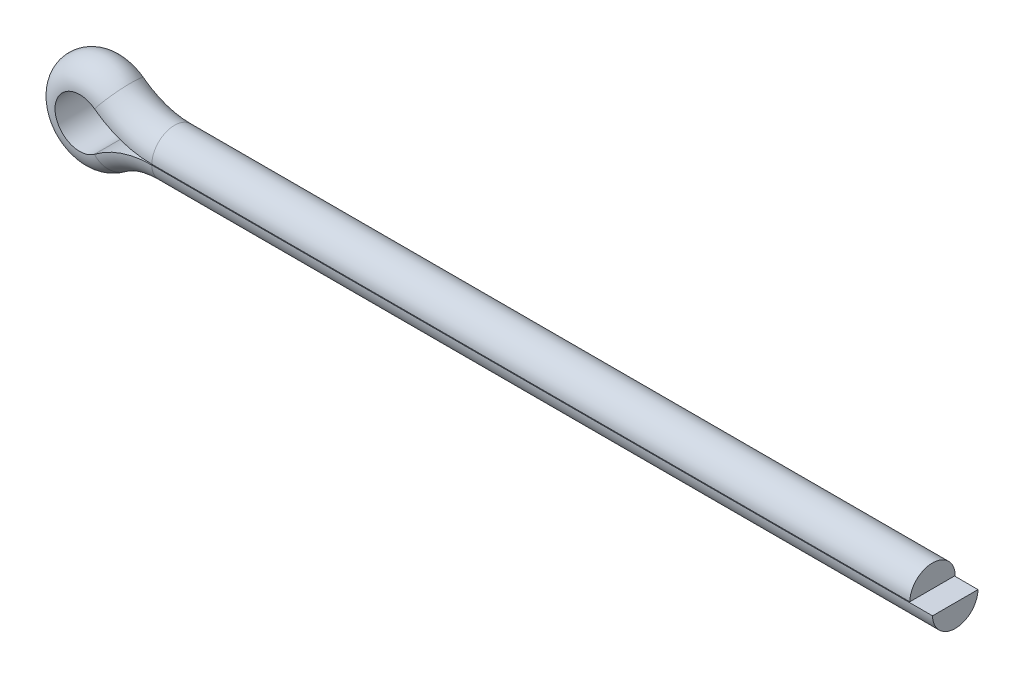
SolidWorks part; units mm, degrees
ref_plane "Front" through (0, 0, 0) normal (0, 0, 1) x (1, 0, 0)
ref_plane "Top" through (0, 0, 0) normal (0, 1, 0) x (1, 0, 0)
ref_plane "Right" through (0, 0, 0) normal (1, 0, 0) x (0, 0, -1)
sketch "Sketch1" plane through (0, 0, 0) normal (0, 0, 1) x (1, 0, 0)
  line L0 (-55.6343, 0) -> (1.524, 0) construction
  line L1 (-50.8, -0.0254) -> (1.524, -0.0254)
  line L2 (-53.9835, 0.0254) -> (1.524, 0.0254) construction
  line L3 (-50.8, 0.0254) -> (0, 0.0254)
  line L4 (-11.4985, 0.0254) -> (1.524, 0.0254) construction
  line L5 (-11.4985, -0.0254) -> (1.524, -0.0254) construction
  line L6 (-55.6343, 1.5875) -> (-55.6343, 0) construction
  line L7 (-55.6343, 1.5875) -> (-55.6343, 3.175) construction
  line L8 (-11.4985, 0) -> (1.524, 0) construction
  line L9 (0, 0.0254) -> (0, 0) construction
  line L10 (-55.6343, 0) -> (-55.6343, -3.175) construction
  line L11 (-50.8, 1.4986) -> (-50.8, -1.5494) construction
  arc A1 (-54.6367, 1.3156) -> (-54.6367, -1.3156) centre (-55.6343, 0) ccw
  arc A2 (-50.8, -0.0254) -> (-54.6367, -1.3156) centre (-50.8, -6.3754) ccw
  arc A3 (-54.6367, 1.3156) -> (-50.8, 0.0254) centre (-50.8, 6.3754) ccw
  circle A4 centre (-55.6343, 0) radius 3.175 construction
  point P15 (0, 0.0254)
  point P26 (-50.8, -0.0254)
  dimension "D6" = 6.35
  dimension "ExtendedProngLength" = 1.524
  dimension "Length" = 50.8
  dimension "Diameter" = 3.048
  dimension "Head Diameter" = 6.35
  dimension "D1" = 1.524
  dimension "D4" = 0.0254
  dimension "D5" = 0.0254
sketch "Sketch2" plane through (0, 0, 0) normal (1, 0, 0) x (0, 0, -1)
  line L0 (-1.5238, 0.0254) -> (1.5238, 0.0254)
  line L1 (0, 1.524) -> (0, -1.524) construction
  circle A1 centre (0, 0) radius 1.524 construction
  arc A2 (-1.5238, 0.0254) -> (1.5238, 0.0254) centre (0, 0) cw
  point P5 (0, 0)
  dimension "WireWidth" = 3.048
sketch "Sketch3" plane through (0, 0, 0) normal (0, 0, 1) x (1, 0, 0)
  line L0 (-50.8, 0.0254) -> (0, 0.0254) construction
  line L1 (-50.8, -0.0254) -> (1.524, -0.0254) construction
  line L2 (-50.8, 0.0254) -> (0, 0.0254)
  line L3 (-50.8, -0.0254) -> (1.524, -0.0254)
  arc A0 (-50.8, -0.0254) -> (-54.6367, -1.3156) centre (-50.8, -6.3754) ccw construction
  arc A1 (-54.6367, 1.3156) -> (-54.6367, -1.3156) centre (-55.6343, 0) ccw construction
  arc A2 (-54.6367, 1.3156) -> (-50.8, 0.0254) centre (-50.8, 6.3754) ccw construction
  arc A3 (-50.8, -0.0254) -> (-54.6367, -1.3156) centre (-50.8, -6.3754) ccw
  arc A4 (-54.6367, 1.3156) -> (-54.6367, -1.3156) centre (-55.6343, 0) ccw
  arc A5 (-54.6367, 1.3156) -> (-50.8, 0.0254) centre (-50.8, 6.3754) ccw
sketch "Sketch4" plane through (0, 0, 0) normal (1, 0, 0) x (0, 0, -1)
  line L0 (-1.5238, 0.0254) -> (1.5238, 0.0254) construction
  line L1 (-1.5238, 0.0254) -> (1.5238, 0.0254)
  arc A2 (1.5238, 0.0254) -> (-1.5238, 0.0254) centre (0, 0) ccw construction
  arc A3 (1.5238, 0.0254) -> (-1.5238, 0.0254) centre (0, 0) ccw
sweep "Sweep1" add profiles "Sketch4" path "Sketch3"
equation "\"WireWidth@Sketch2\"=\"Diameter@Sketch1\""
equation "\"D1@Sketch1\"=\"Diameter@Sketch1\"/2"
